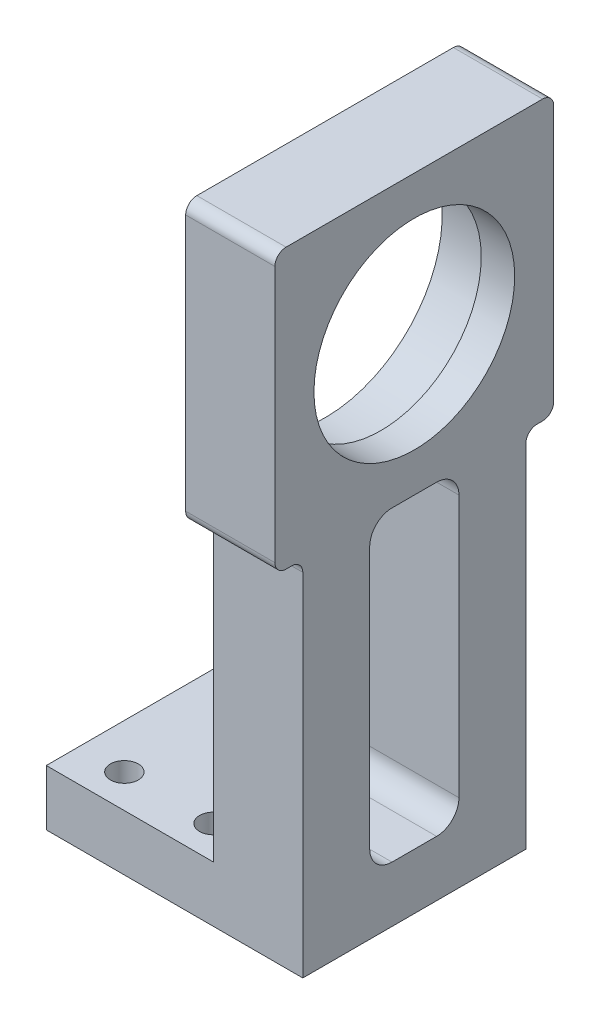
SolidWorks part; units mm, degrees
ref_plane "Front Plane" through (0, 0, 0) normal (0, 0, 1) x (1, 0, 0)
ref_plane "Top Plane" through (0, 0, 0) normal (0, 1, 0) x (1, 0, 0)
ref_plane "Right Plane" through (0, 0, 0) normal (1, 0, 0) x (0, 0, -1)
sketch "Sketch1" plane through (0, 0, 0) normal (0, 1, 0) x (1, 0, 0)
  line L1 (0, 0) -> (20, 0)
  line L2 (0, 0) -> (0, 20)
  line L3 (0, 20) -> (20, 20)
  line L4 (20, 0) -> (20, 20)
  dimension "D1" = 20
  dimension "D2" = 20
extrude "Boss-Extrude1" add sketch "Sketch1" along normal blind 5
ref_plane "Plane1" through (0, 0, -10) normal (0, 0, 1) x (1, 0, 0)
sketch "Sketch2" plane through (20, 0, 0) normal (1, 0, 0) x (0, 0, -1)
  line L0 (0, 5) -> (20, 5) construction
  line L1 (0, 0) -> (20, 0)
  line L2 (0, 0) -> (0, 32.5)
  line L3 (0, 32.5) -> (20, 32.5)
  line L4 (20, 0) -> (20, 32.5)
  line L5 (14, 32.5) -> (6, 32.5)
  line L6 (14, 32.5) -> (14, 5)
  line L7 (-2.5, 32.5) -> (22.5, 32.5)
  line L8 (-2.5, 32.5) -> (-2.5, 57.5)
  line L9 (-2.5, 57.5) -> (22.5, 57.5)
  line L10 (22.5, 32.5) -> (22.5, 57.5)
  line L11 (14, 5) -> (6, 5)
  line L12 (6, 32.5) -> (6, 5)
  point P10 (10, 32.5)
  line M9 (0, 0) -> (20, 0)
  line M10 (20, 0) -> (20, 5)
  line M11 (20, 5) -> (0, 5)
  line M12 (0, 5) -> (0, 0)
  dimension "D1" = 32.5
  dimension "D2" = 25
  dimension "D3" = 25
  dimension "D4" = 6
  dimension "D5" = 6
extrude "Boss-Extrude2" add sketch "Sketch2" along normal blind 3 and the other way blind 5 contours L3 L6 L4 M11 | L12 L3 L2 M11 | M12 M9 M10 M11 | L7 L10 L9 L8 L3
sketch "Sketch4" plane through (0, 5, 0) normal (0, 1, 0) x (1, 0, 0)
  line L1 (0, 0) -> (15, 0) construction
  line L2 (-2.75, 10) -> (2.75, 10) construction
  line L3 (15, 6) -> (15, 0) construction
  circle A0 centre (12, 3) radius 1.25
  circle A1 centre (4, 3) radius 1.25
  circle A2 centre (12, 17) radius 1.25
  circle A3 centre (4, 17) radius 1.25
  dimension "D1" = 2.5
  dimension "D2" = 3
  dimension "D3" = 3
  dimension "D4" = 8
extrude "Cut-Extrude1" cut sketch "Sketch4" against normal up to next
sketch "Sketch8" plane through (15, 0, 0) normal (-1, 0, 0) x (0, 0, 1)
  line L0 (2.5, 32.5) -> (2.5, 57.5) construction
  line L1 (2.5, 57.5) -> (-22.5, 57.5) construction
  circle A0 centre (-10, 45) radius 10.5
  point P2 (2.5, 45)
  point P7 (-10, 57.5)
  dimension "D1" = 21
extrude "Cut-Extrude4" cut sketch "Sketch8" against normal blind 5
sketch "Sketch9" plane through (20, 0, 0) normal (-1, 0, 0) x (0, 0, 1)
  circle A0 centre (-10, 45) radius 9
  circle A1 centre (-10, 45) radius 10.5 construction
  dimension "D1" = 18
extrude "Cut-Extrude5" cut sketch "Sketch9" against normal up to next
fillet "Fillet2" radius 1 6 edges at (19, 32.5, -20) (19, 32.5, 0) (19, 32.5, 2.5) (19, 57.5, 2.5) (19, 57.5, -22.5) (19, 32.5, -22.5)
fillet "Fillet3" radius 2 4 edges at (19, 5, -6) (19, 32.5, -6) (19, 5, -14) (19, 32.5, -14)
